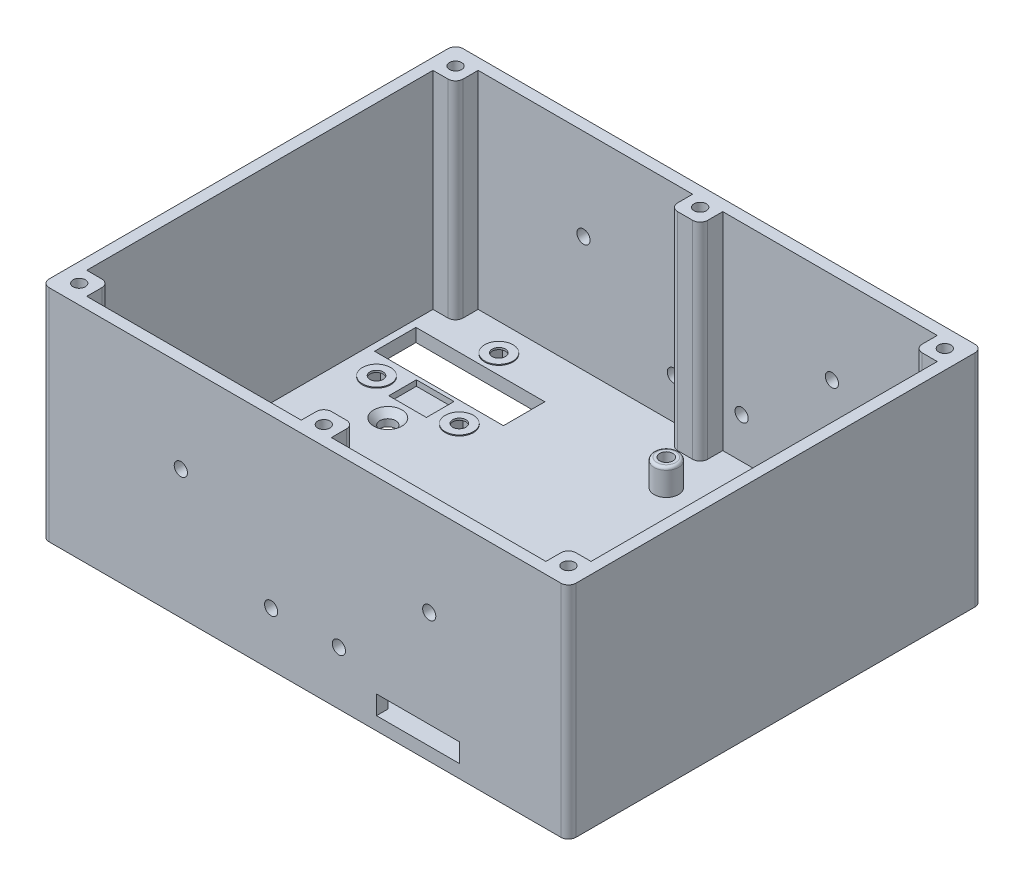
SolidWorks part; units mm, degrees
ref_plane "Front Plane" through (0, 0, 0) normal (0, 0, 1) x (1, 0, 0)
ref_plane "Top Plane" through (0, 0, 0) normal (0, 1, 0) x (1, 0, 0)
ref_plane "Right Plane" through (0, 0, 0) normal (1, 0, 0) x (0, 0, -1)
sketch "Sketch1" plane through (0, 0, 0) normal (0, 1, 0) x (1, 0, 0)
  line L1 (70, -55) -> (-70, -55)
  line L2 (70, -55) -> (70, 55)
  line L3 (70, 55) -> (-70, 55)
  line L4 (-70, -55) -> (-70, 55)
  line L5 (70, -55) -> (-70, 55) construction
  line L6 (70, 55) -> (-70, -55) construction
  point P0 (0, 0)
  dimension "D1" = 110
  dimension "D2" = 140
extrude "Bottom" add sketch "Sketch1" along normal blind 3.5
sketch "Sketch3" plane through (0, 3.5, 0) normal (0, 1, 0) x (1, 0, 0)
  line L0 (-70, 55) -> (70, 55)
  line L1 (70, 55) -> (70, -55)
  line L2 (70, -55) -> (-70, -55)
  line L3 (-70, -55) -> (-70, 55)
  line L4 (-61, 52) -> (-4, 52)
  line L5 (67, 46) -> (67, -46)
  line L6 (61, -52) -> (4, -52)
  line L7 (0, 55) -> (0, -55) construction
  line L8 (-67, 46) -> (-61, 46)
  line L9 (-61, 46) -> (-61, 52)
  line L10 (61, 52) -> (61, 46)
  line L11 (61, 46) -> (67, 46)
  line L12 (67, -46) -> (61, -46)
  line L13 (61, -46) -> (61, -52)
  line L14 (-67, -46) -> (-61, -46)
  line L15 (-61, -46) -> (-61, -52)
  line L16 (-67, -46) -> (-67, 46)
  line L17 (0, 0) -> (67, 0) construction
  line L18 (4, -52) -> (4, -46)
  line L19 (-4, 52) -> (-4, 46)
  line L20 (-4, 46) -> (4, 46)
  line L21 (4, 52) -> (4, 46)
  line L22 (0, 46) -> (0, 42.7097) construction
  line L23 (4, 52) -> (61, 52)
  line L24 (-4, -46) -> (4, -46)
  line L25 (-4, -52) -> (-4, -46)
  line L26 (-4, -52) -> (-61, -52)
  dimension "D1" = 3
  dimension "D2" = 3
  dimension "D3" = 3
  dimension "D4" = 3
  dimension "D5" = 6
  dimension "D6" = 8
extrude "Wall" add sketch "Sketch3" along normal blind 55
sketch "Sketch4" plane through (0, 58.5, 0) normal (0, 1, 0) x (1, 0, 0)
  line L0 (-70, 55) -> (-70, -55) construction
  line L1 (70, 55) -> (-70, 55) construction
  line L2 (70, -55) -> (70, 55) construction
  line L3 (-70, -55) -> (70, -55) construction
  line L4 (0, 55) -> (0, 30.3541) construction
  line L5 (70, 0) -> (33.8613, 0) construction
  circle A0 centre (-65, 50) radius 1.625
  circle A1 centre (65, 50) radius 1.625
  circle A2 centre (65, -50) radius 1.625
  circle A3 centre (-65, -50) radius 1.625
  circle A4 centre (0, 50) radius 1.625
  circle A5 centre (0, -50) radius 1.625
  dimension "D1" = 3.25
  dimension "D4" = 5
  dimension "D2" = 5
  dimension "D3" = 5
  dimension "D5" = 5
extrude "Top Plate Screw Holes" cut sketch "Sketch4" against normal blind 30 draft 1
fillet "Fillet14" radius 2 1 edges at (-4, 31, 46)
fillet "Fillet13" radius 2 1 edges at (4, 31, 46)
fillet "Fillet12" radius 2 1 edges at (-4, 31, -46)
fillet "Fillet11" radius 2 1 edges at (4, 31, -46)
fillet "Fillet1" radius 2 1 edges at (-61, 31, 46)
fillet "Fillet2" radius 2 1 edges at (61, 31, 46)
fillet "Fillet3" radius 2 1 edges at (61, 31, -46)
fillet "Fillet4" radius 2 1 edges at (-61, 31, -46)
fillet "Fillet5" radius 2 1 edges at (-70, 29.25, -55)
fillet "Fillet6" radius 2 1 edges at (70, 29.25, -55)
fillet "Fillet7" radius 2 1 edges at (70, 29.25, 55)
fillet "Fillet8" radius 2 1 edges at (-70, 29.25, 55)
sketch "M4 Mount" plane through (0, 3.5, 0) normal (0, -1, 0) x (1, 0, 0)
  line L0 (70, 53) -> (70, -53) construction
  line L1 (0, 0) -> (23.8675, 0) construction
  line L2 (0, 0) -> (0, -19.9393) construction
  circle A0 centre (48, -15) radius 2.1
  circle A1 centre (48, 20) radius 2.1
  circle A2 centre (-48, 20) radius 2.1
  circle A3 centre (-48, -15) radius 2.1
  dimension "D1" = 4.2
  dimension "D2" = 22
  dimension "D3" = 15
  dimension "D4" = 20
extrude "M4 Mount Cut" cut sketch "M4 Mount" along normal through all
sketch "M4 Screw Heads" plane through (0, 3.5, 0) normal (0, 1, 0) x (1, 0, 0)
  circle A0 centre (48, -20) radius 3.75
  circle A1 centre (48, 15) radius 3.75
  circle A2 centre (-48, 15) radius 3.75
  circle A3 centre (-48, -20) radius 3.75
  dimension "D1" = 7.5
extrude "Cut-Extrude3" cut sketch "M4 Screw Heads" against normal blind 10 draft 45
sketch "Sketch7" plane through (0, 0, 0) normal (0, -1, 0) x (1, 0, 0)
  line L2 (67, 46) -> (67, -46) construction
  line L5 (61, -52) -> (4, -52) construction
  circle A0 centre (41, -32) radius 7.5
  dimension "D1" = 15
  dimension "D2" = 26
  dimension "D3" = 20
extrude "USB Cabel Cut" cut sketch "Sketch7" against normal through all
fillet "Fillet9" radius 1 1 edges at (41, 0, -39.5)
fillet "Fillet10" radius 1 1 edges at (41, 3.5, -24.5)
sketch "Sketch14" plane through (0, 3.5, 0) normal (0, 1, 0) x (1, 0, 0)
  line L0 (67, -46) -> (67, 46) construction
  line L1 (59, 30) -> (51, 30)
  line L2 (59, 30) -> (59, 37)
  line L3 (59, 37) -> (51, 37)
  line L4 (51, 30) -> (51, 37)
  line L5 (59, 30) -> (51, 37) construction
  line L6 (59, 37) -> (51, 30) construction
  line L7 (61, 52) -> (4, 52) construction
  point P0 (0, 33.9149)
  dimension "D1" = 7
  dimension "D2" = 8
  dimension "D3" = 8
  dimension "D4" = 15
extrude "Boss-Extrude1" add sketch "Sketch14" along normal blind 6
sketch "Sketch16" plane through (18.1808, 0, -30) normal (0, 0, -1) x (-1, 0, 0)
  line L1 (-38.8192, 3.5) -> (-34.8192, 3.5)
  line L2 (-38.8192, 3.5) -> (-38.8192, 6.5)
  line L3 (-38.8192, 6.5) -> (-34.8192, 6.5)
  line L4 (-34.8192, 3.5) -> (-34.8192, 6.5)
  line L5 (-36.8192, 3.5) -> (-36.8192, 6.5) construction
  line L6 (-32.8192, 3.5) -> (-40.8192, 3.5) construction
  dimension "D1" = 4
  dimension "D3" = 3
extrude "Cut-Extrude6" cut sketch "Sketch16" along normal up to surface (7 mm away) up to face at (55, 6.5, -37)
sketch "Sketch9" plane through (0, 3.5, 0) normal (0, 1, 0) x (1, 0, 0)
  line L2 (5, 36) -> (-8.5, 36) construction
  line L3 (-8.5, 36) -> (-8.5, -39) construction
  line L6 (-8.5, -39) -> (10.6129, -39) construction
  line L7 (-2, -46) -> (2, -46) construction
  line L9 (0, 46) -> (0, 26) construction
  line L10 (2, 46) -> (-2, 46) construction
  circle A0 centre (-8.5, -39) radius 3.25
  circle A5 centre (5, 36) radius 3.25
  point P3 (0, -46)
  dimension "D1" = 6.5
  dimension "D4" = 7
  dimension "D2" = 13.5
  dimension "D3" = 75
  dimension "D5" = 5
extrude "Curcuit Board Mount Posts EXT" add sketch "Sketch9" along normal offset from surface (7 mm away) 1 up to face at (55, 9.5, -33.5) offset beyond the face yes
sketch "Sketch10" plane through (0, 10.5, 0) normal (0, 1, 0) x (1, 0, 0)
  circle A0 centre (5, 36) radius 1.75
  circle A1 centre (-8.5, -39) radius 1.75
  dimension "D1" = 3.5
extrude "M3 Screw Curcuit Mount CUT" cut sketch "Sketch10" against normal through all
sketch "Sketch11" plane through (0, 0, 0) normal (0, -1, 0) x (1, 0, 0)
  line L1 (-10.941, 37.7335) -> (-8.6237, 36.2528)
  line L2 (-8.6237, 36.2528) -> (-6.1827, 37.5193)
  line L3 (-6.1827, 37.5193) -> (-6.059, 40.2665)
  line L4 (-6.059, 40.2665) -> (-8.3763, 41.7472)
  line L5 (-8.3763, 41.7472) -> (-10.8173, 40.4807)
  line L6 (-10.8173, 40.4807) -> (-10.941, 37.7335)
  line L7 (5, -39.1754) -> (7.75, -37.5877)
  line L8 (7.75, -37.5877) -> (7.75, -34.4123)
  line L9 (7.75, -34.4123) -> (5, -32.8246)
  line L10 (5, -32.8246) -> (2.25, -34.4123)
  line L11 (2.25, -34.4123) -> (2.25, -37.5877)
  line L12 (2.25, -37.5877) -> (5, -39.1754)
  circle A0 centre (-8.5, 39) radius 2.3816 construction
  circle A1 centre (5, -36) radius 2.75 construction
  dimension "D1" = 5.5
  dimension "D2" = 5.5
extrude "M3 Head Circuit Mount CUT" cut sketch "Sketch11" against normal offset from surface (3.25 mm away) 0.25
fillet "Fillet15" radius 0.75 1 edges at (5, 10.5, -32.75)
fillet "Fillet16" radius 0.75 1 edges at (-8.5, 10.5, 42.25)
sketch "Sketch18" plane through (0, 0, -55) normal (0, 0, -1) x (-1, 0, 0)
  line L0 (-68, 29.25) -> (68, 29.25) construction
  line L1 (-68, 58.5) -> (-68, 0) construction
  line L2 (68, 0) -> (68, 58.5) construction
  line L3 (0, 58.5) -> (0, 29.25) construction
  line L4 (-68, 58.5) -> (68, 58.5) construction
  line L7 (-4, 58.5) -> (-4, 3.5) construction
  circle A0 centre (-33, 34.25) radius 1.75
  circle A1 centre (33, 34.25) radius 1.75
  circle A2 centre (-9, 14.25) radius 1.75
  circle A3 centre (9, 14.25) radius 1.75
  dimension "D1" = 3.5
  dimension "D2" = 33
  dimension "D3" = 33
  dimension "D4" = 5
  dimension "D5" = 15
  dimension "D6" = 5
extrude "TOP-Screw" cut sketch "Sketch18" against normal up to surface (3 mm away) up to face at (-32.5, 31, -52)
sketch "Sketch19" plane through (0, 0, -52) normal (0, 0, 1) x (1, 0, 0)
  line L0 (61, 3.5) -> (4, 3.5) construction
  line L1 (41, 3.5) -> (19, 3.5)
  line L2 (41, 3.5) -> (41, 8.5)
  line L3 (41, 8.5) -> (19, 8.5)
  line L4 (19, 3.5) -> (19, 8.5)
  line L5 (61, 58.5) -> (61, 3.5) construction
  line L6 (4, 58.5) -> (4, 3.5) construction
  dimension "D1" = 20
  dimension "D2" = 15
  dimension "D3" = 5
extrude "TOP-Cables" cut sketch "Sketch19" against normal blind 10
sketch "Sketch20" plane through (0, 0, 55) normal (0, 0, 1) x (1, 0, 0)
  line L1 (19, 3.5) -> (41, 3.5)
  line L2 (19, 3.5) -> (19, 8.5)
  line L3 (19, 8.5) -> (41, 8.5)
  line L4 (41, 3.5) -> (41, 8.5)
  line L5 (41, 8.5) -> (19, 8.5) construction
  line L7 (41, 3.5) -> (41, 8.5) construction
  line L9 (19, 8.5) -> (19, 3.5) construction
extrude "Bottom-Cables" cut sketch "Sketch20" against normal up to surface (3 mm away) up to face at (32.5, 31, 52)
sketch "Sketch21" plane through (0, 0, 55) normal (0, 0, 1) x (1, 0, 0)
  circle A0 centre (-33, 34.25) radius 1.75
  circle A1 centre (-9, 14.25) radius 1.75
  circle A2 centre (9, 14.25) radius 1.75
  circle A3 centre (33, 34.25) radius 1.75
  circle A5 centre (33, 34.25) radius 1.75 construction
  circle A6 centre (9, 14.25) radius 1.75 construction
  circle A7 centre (-9, 14.25) radius 1.75 construction
  circle A8 centre (-33, 34.25) radius 1.75 construction
extrude "Bottom-Screw" cut sketch "Sketch21" against normal up to surface (3 mm away) up to face at (-32.5, 31, 52)
sketch "Sketch22" plane through (0, 3.5, 0) normal (0, 1, 0) x (1, 0, 0)
  line L0 (-48, 44.5) -> (-48, 23) construction
  line L1 (-48, 23) -> (-59, 23) construction
  line L3 (-4, 52) -> (-61, 52) construction
  line L4 (-67, 46) -> (-67, -46) construction
  line L13 (-65.125, 28.6) -> (-30.875, 28.6)
  line L14 (-48, 28.6) -> (-48, 34.2847) construction
  line L15 (-65.125, 28.6) -> (-65.125, 39.6)
  line L16 (-65.125, 39.6) -> (-30.875, 39.6)
  line L17 (-30.875, 39.6) -> (-30.875, 28.6)
  dimension "D3" = 21.5
  dimension "D4" = 11
  dimension "D7" = 7.5
  dimension "D8" = 8
  dimension "D19" = 5.6
  dimension "D20" = 34.25
  dimension "D21" = 11
sketch "Sketch23" plane through (0, 3.5, 0) normal (0, 1, 0) x (1, 0, 0)
  line L0 (-48, 44.5) -> (-48, 23) construction
  line L1 (-59, 23) -> (-37, 23) construction
  circle A0 centre (-48, 44.5) radius 1.75
  circle A1 centre (-37, 23) radius 1.75
  circle A2 centre (-59, 23) radius 1.75
  dimension "D1" = 3.5
sketch "Sketch24" plane through (0, 3.5, 0) normal (0, 1, 0) x (1, 0, 0)
  circle A0 centre (-59, 23) radius 3.75
  circle A1 centre (-48, 44.5) radius 3.75
  circle A2 centre (-37, 23) radius 3.75
  circle A4 centre (-59, 23) radius 1.75 construction
  dimension "D1" = 2
extrude "Connectors Cut" cut sketch "Sketch22" against normal up to surface (3.5 mm away) up to face at (5, 0, -36)
extrude "Standoffs" add sketch "Sketch24" along normal blind 0.25
extrude "M3 Screw Hole" cut sketch "Sketch23" against normal through all both and the other way through all
sketch "Sketch25" plane through (0, 0, 0) normal (0, -1, 0) x (1, 0, 0)
  line L1 (-39.75, -23) -> (-38.375, -25.3816)
  line L2 (-38.375, -25.3816) -> (-35.625, -25.3816)
  line L3 (-35.625, -25.3816) -> (-34.25, -23)
  line L4 (-34.25, -23) -> (-35.625, -20.6184)
  line L5 (-35.625, -20.6184) -> (-38.375, -20.6184)
  line L6 (-38.375, -20.6184) -> (-39.75, -23)
  line L7 (-60.375, -25.3816) -> (-57.625, -25.3816)
  line L8 (-57.625, -25.3816) -> (-56.25, -23)
  line L9 (-56.25, -23) -> (-57.625, -20.6184)
  line L10 (-57.625, -20.6184) -> (-60.375, -20.6184)
  line L11 (-60.375, -20.6184) -> (-61.75, -23)
  line L12 (-61.75, -23) -> (-60.375, -25.3816)
  line L13 (-49.375, -46.8816) -> (-46.625, -46.8816)
  line L14 (-46.625, -46.8816) -> (-45.25, -44.5)
  line L15 (-45.25, -44.5) -> (-46.625, -42.1184)
  line L16 (-46.625, -42.1184) -> (-49.375, -42.1184)
  line L17 (-49.375, -42.1184) -> (-50.75, -44.5)
  line L18 (-50.75, -44.5) -> (-49.375, -46.8816)
  circle A0 centre (-37, -23) radius 2.3816 construction
  circle A1 centre (-59, -23) radius 2.3816 construction
  circle A2 centre (-48, -44.5) radius 2.3816 construction
  dimension "D1" = 5.5
  dimension "D2" = 5.5
  dimension "D3" = 5.5
extrude "M3 Nut" cut sketch "Sketch25" against normal offset from surface (3.25 mm away) 0.25 up to face at (-48, 3.5, -40.75)
sketch "Sketch26" plane through (0, 3.5, 0) normal (0, 1, 0) x (1, 0, 0)
  line L0 (-59, 23) -> (-39, 23) construction
  line L1 (-53, 27.6) -> (-43, 27.6)
  line L2 (-53, 27.6) -> (-53, 20.25)
  line L3 (-53, 20.25) -> (-43, 20.25)
  line L4 (-43, 27.6) -> (-43, 20.25)
  line L5 (-53, 23) -> (-43, 23) construction
  line L6 (-65.125, 28.6) -> (-30.875, 28.6) construction
  dimension "D5" = 6
  dimension "D1" = 2.75
  dimension "D2" = 10
  dimension "D3" = 20
  dimension "D4" = 1
extrude "Room for PCB pins" cut sketch "Sketch26" against normal blind 1.5
equation "\"BOXWALL\"=3"
equation "\"D2@Sketch3\"= \"BOXWALL\""
equation "\"D3@Sketch3\"=\"BOXWALL\""
equation "\"D4@Sketch3\"=\"BOXWALL\""
equation "\"SCREW_M3\"=3.5"
equation "\"D1@Sketch10\"=\"SCREW_M3\""
equation "\"SCREW_M3_HEAD\"=5.5"
equation "\"D1@Sketch11\"=\"SCREW_M3_HEAD\""
equation "\"D1@Sketch18\"=\"SCREW_M3\""
equation "\"D2@Sketch11\"=\"SCREW_M3_HEAD\""
equation "\"D1@Sketch23\"=\"SCREW_M3\""
equation "\"D1@Sketch25\"=\"SCREW_M3_HEAD\""
equation "\"D2@Sketch25\"=\"SCREW_M3_HEAD\""
equation "\"D3@Sketch25\"=\"SCREW_M3_HEAD\""
